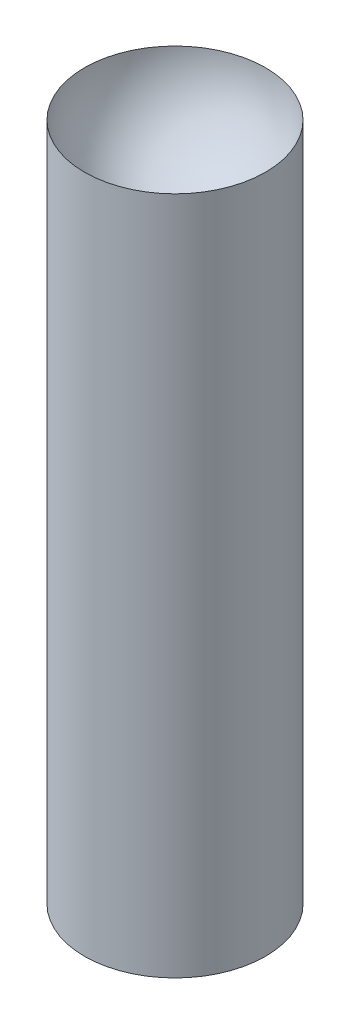
SolidWorks part; units mm, degrees
ref_plane "Front Plane" through (0, 0, 0) normal (0, 0, 1) x (1, 0, 0)
ref_plane "Top Plane" through (0, 0, 0) normal (0, 1, 0) x (1, 0, 0)
ref_plane "Right Plane" through (0, 0, 0) normal (1, 0, 0) x (0, 0, -1)
sketch "Sketch1" plane through (0, 0, 0) normal (0, 1, 0) x (1, 0, 0)
  circle A0 centre (0, 0) radius 10.16
extrude "Boss-Extrude1" add sketch "Sketch1" along normal blind 76.2
sketch "Sketch2" plane through (0, 76.2, 0) normal (0, 1, 0) x (1, 0, 0)
  line L0 (0, 10.16) -> (0, -10.16) construction
  line L1 (0, 10.16) -> (0, -10.16)
  arc A0 (0, -10.16) -> (0, 10.16) centre (0, 0) ccw
revolve "Cut-Revolve1" cut sketch "Sketch2" angle 360 about L0
